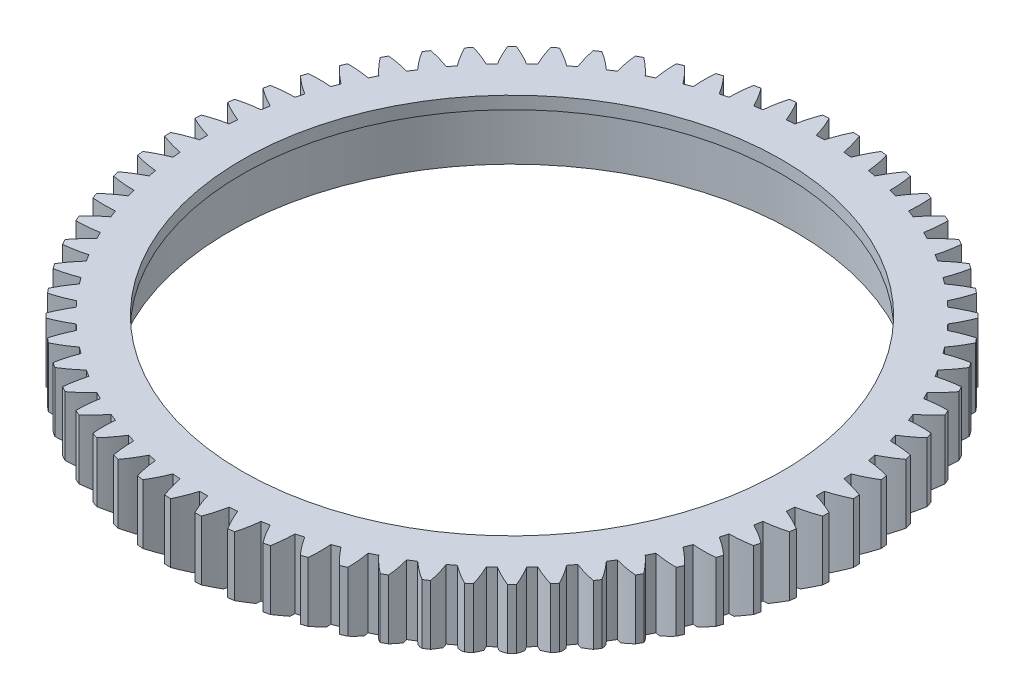
SolidWorks part; units mm, degrees
ref_plane "Front Plane" through (0, 0, 0) normal (0, 0, 1) x (1, 0, 0)
ref_plane "Top Plane" through (0, 0, 0) normal (0, 1, 0) x (1, 0, 0)
ref_plane "Right Plane" through (0, 0, 0) normal (1, 0, 0) x (0, 0, -1)
sketch "Sketch1" plane through (0, 0, 0) normal (0, 1, 0) x (1, 0, 0)
  circle A0 centre (0, 0) radius 53
  circle A1 centre (0, 0) radius 43
  dimension "D1" = 106
  dimension "D2" = 86
extrude "Boss-Extrude1" add sketch "Sketch1" along normal blind 11
sketch "Sketch3" plane through (0, 0, 0) normal (0, -1, 0) x (1, 0, 0)
  circle A0 centre (0, 0) radius 45.1
  dimension "D1" = 90.2
extrude "Cut-Extrude2" cut sketch "Sketch3" against normal blind 9
sketch "Sketch4" plane through (0, 0, 0) normal (0, -1, 0) x (1, 0, 0)
  arc A0 (-52.4646, 1.9286) -> (-49.1199, 0.6319) centre (-43.4466, 20.2271) ccw
  arc A1 (-49.1199, 0.6319) -> (-49.1199, -0.6319) centre (0, 0) ccw
  arc A2 (-49.1199, -0.6319) -> (-52.4646, -1.9286) centre (-43.4466, -20.2271) ccw
  arc A3 (-52.4646, -1.9286) -> (-52.4187, -2.9204) centre (0, 0) ccw
  arc A4 (-52.4187, -2.9204) -> (-48.9687, -3.903) centre (-45.1276, 16.1321) ccw
  arc A5 (-48.9687, -3.903) -> (-48.8521, -5.1614) centre (0, 0) ccw
  arc A6 (-48.8521, -5.1614) -> (-52.0628, -6.7612) centre (-41.3949, -24.1496) ccw
  arc A7 (-52.0628, -6.7612) -> (-51.9256, -7.7446) centre (0, 0) ccw
  arc A8 (-51.9256, -7.7446) -> (-48.3997, -8.4046) centre (-46.4235, 11.8994) ccw
  arc A9 (-48.3997, -8.4046) -> (-48.1675, -9.6469) centre (0, 0) ccw
  arc A10 (-48.1675, -9.6469) -> (-51.2169, -11.5361) centre (-38.9901, -27.866) ccw
  arc A11 (-51.2169, -11.5361) -> (-50.9896, -12.5026) centre (0, 0) ccw
  arc A12 (-50.9896, -12.5026) -> (-47.4177, -12.8345) centre (-47.3234, 7.5653) ccw
  arc A13 (-47.4177, -12.8345) -> (-47.0719, -14.0501) centre (0, 0) ccw
  arc A14 (-47.0719, -14.0501) -> (-49.934, -16.2126) centre (-36.2526, -31.3447) ccw
  arc A15 (-49.934, -16.2126) -> (-49.6184, -17.154) centre (0, 0) ccw
  arc A16 (-49.6184, -17.154) -> (-46.0312, -17.1549) centre (-47.8196, 3.1665) ccw
  arc A17 (-46.0312, -17.1549) -> (-45.5747, -18.3334) centre (0, 0) ccw
  arc A18 (-45.5747, -18.3334) -> (-48.2251, -20.7508) centre (-33.2058, -34.5559) ccw
  arc A19 (-48.2251, -20.7508) -> (-47.824, -21.659) centre (0, 0) ccw
  arc A20 (-47.824, -21.659) -> (-44.252, -21.329) centre (-47.9078, -1.2592) ccw
  arc A21 (-44.252, -21.329) -> (-43.6887, -22.4603) centre (0, 0) ccw
  arc A22 (-43.6887, -22.4603) -> (-46.1047, -25.1119) centre (-29.8758, -37.4724) ccw
  arc A23 (-46.1047, -25.1119) -> (-45.6216, -25.9793) centre (0, 0) ccw
  arc A24 (-45.6216, -25.9793) -> (-42.0953, -25.3211) centre (-47.5872, -5.6742) ccw
  arc A25 (-42.0953, -25.3211) -> (-41.43, -26.3956) centre (0, 0) ccw
  arc A26 (-41.43, -26.3956) -> (-43.591, -29.2588) centre (-26.2908, -40.0691) ccw
  arc A27 (-43.591, -29.2588) -> (-43.0299, -30.0779) centre (0, 0) ccw
  arc A28 (-43.0299, -30.0779) -> (-39.5794, -29.0971) centre (-46.8607, -10.0408) ccw
  arc A29 (-39.5794, -29.0971) -> (-38.8178, -30.1056) centre (0, 0) ccw
  arc A30 (-38.8178, -30.1056) -> (-40.7054, -33.156) centre (-22.4815, -42.324) ccw
  arc A31 (-40.7054, -33.156) -> (-40.0711, -33.9199) centre (0, 0) ccw
  arc A32 (-40.0711, -33.9199) -> (-36.7258, -32.6249) centre (-45.7343, -14.3217) ccw
  arc A33 (-36.7258, -32.6249) -> (-35.8744, -33.5589) centre (0, 0) ccw
  arc A34 (-35.8744, -33.5589) -> (-37.4725, -36.7704) centre (-18.4805, -44.2178) ccw
  arc A35 (-37.4725, -36.7704) -> (-36.7704, -37.4725) centre (0, 0) ccw
  arc A36 (-36.7704, -37.4725) -> (-33.5589, -35.8744) centre (-44.2178, -18.4805) ccw
  arc A37 (-33.5589, -35.8744) -> (-32.6249, -36.7258) centre (0, 0) ccw
  arc A38 (-32.6249, -36.7258) -> (-33.9199, -40.0711) centre (-14.3217, -45.7343) ccw
  arc A39 (-33.9199, -40.0711) -> (-33.156, -40.7054) centre (0, 0) ccw
  arc A40 (-33.156, -40.7054) -> (-30.1056, -38.8178) centre (-42.324, -22.4815) ccw
  arc A41 (-30.1056, -38.8178) -> (-29.0971, -39.5794) centre (0, 0) ccw
  arc A42 (-29.0971, -39.5794) -> (-30.0779, -43.0299) centre (-10.0408, -46.8607) ccw
  arc A43 (-30.0779, -43.0299) -> (-29.2588, -43.591) centre (0, 0) ccw
  arc A44 (-29.2588, -43.591) -> (-26.3956, -41.43) centre (-40.0691, -26.2908) ccw
  arc A45 (-26.3956, -41.43) -> (-25.3211, -42.0953) centre (0, 0) ccw
  arc A46 (-25.3211, -42.0953) -> (-25.9793, -45.6216) centre (-5.6742, -47.5872) ccw
  arc A47 (-25.9793, -45.6216) -> (-25.1119, -46.1047) centre (0, 0) ccw
  arc A48 (-25.1119, -46.1047) -> (-22.4603, -43.6887) centre (-37.4724, -29.8758) ccw
  arc A49 (-22.4603, -43.6887) -> (-21.329, -44.252) centre (0, 0) ccw
  arc A50 (-21.329, -44.252) -> (-21.659, -47.824) centre (-1.2592, -47.9078) ccw
  arc A51 (-21.659, -47.824) -> (-20.7508, -48.2251) centre (0, 0) ccw
  arc A52 (-20.7508, -48.2251) -> (-18.3334, -45.5747) centre (-34.5559, -33.2058) ccw
  arc A53 (-18.3334, -45.5747) -> (-17.1549, -46.0312) centre (0, 0) ccw
  arc A54 (-17.1549, -46.0312) -> (-17.154, -49.6184) centre (3.1665, -47.8196) ccw
  arc A55 (-17.154, -49.6184) -> (-16.2126, -49.934) centre (0, 0) ccw
  arc A56 (-16.2126, -49.934) -> (-14.0501, -47.0719) centre (-31.3447, -36.2526) ccw
  arc A57 (-14.0501, -47.0719) -> (-12.8345, -47.4177) centre (0, 0) ccw
  arc A58 (-12.8345, -47.4177) -> (-12.5026, -50.9896) centre (7.5653, -47.3234) ccw
  arc A59 (-12.5026, -50.9896) -> (-11.5361, -51.2169) centre (0, 0) ccw
  arc A60 (-11.5361, -51.2169) -> (-9.6469, -48.1675) centre (-27.866, -38.9901) ccw
  arc A61 (-9.6469, -48.1675) -> (-8.4046, -48.3997) centre (0, 0) ccw
  arc A62 (-8.4046, -48.3997) -> (-7.7446, -51.9256) centre (11.8994, -46.4235) ccw
  arc A63 (-7.7446, -51.9256) -> (-6.7612, -52.0628) centre (0, 0) ccw
  arc A64 (-6.7612, -52.0628) -> (-5.1614, -48.8521) centre (-24.1496, -41.3949) ccw
  arc A65 (-5.1614, -48.8521) -> (-3.903, -48.9687) centre (0, 0) ccw
  arc A66 (-3.903, -48.9687) -> (-2.9204, -52.4187) centre (16.1321, -45.1276) ccw
  arc A67 (-2.9204, -52.4187) -> (-1.9286, -52.4646) centre (0, 0) ccw
  arc A68 (-1.9286, -52.4646) -> (-0.6319, -49.1199) centre (-20.2271, -43.4466) ccw
  arc A69 (-0.6319, -49.1199) -> (0.6319, -49.1199) centre (0, 0) ccw
  arc A70 (0.6319, -49.1199) -> (1.9286, -52.4646) centre (20.2271, -43.4466) ccw
  arc A71 (1.9286, -52.4646) -> (2.9204, -52.4187) centre (0, 0) ccw
  arc A72 (2.9204, -52.4187) -> (3.903, -48.9687) centre (-16.1321, -45.1276) ccw
  arc A73 (3.903, -48.9687) -> (5.1614, -48.8521) centre (0, 0) ccw
  arc A74 (5.1614, -48.8521) -> (6.7612, -52.0628) centre (24.1496, -41.3949) ccw
  arc A75 (6.7612, -52.0628) -> (7.7446, -51.9256) centre (0, 0) ccw
  arc A76 (7.7446, -51.9256) -> (8.4046, -48.3997) centre (-11.8994, -46.4235) ccw
  arc A77 (8.4046, -48.3997) -> (9.6469, -48.1675) centre (0, 0) ccw
  arc A78 (9.6469, -48.1675) -> (11.5361, -51.2169) centre (27.866, -38.9901) ccw
  arc A79 (11.5361, -51.2169) -> (12.5026, -50.9896) centre (0, 0) ccw
  arc A80 (12.5026, -50.9896) -> (12.8345, -47.4177) centre (-7.5653, -47.3234) ccw
  arc A81 (12.8345, -47.4177) -> (14.0501, -47.0719) centre (0, 0) ccw
  arc A82 (14.0501, -47.0719) -> (16.2126, -49.934) centre (31.3447, -36.2526) ccw
  arc A83 (16.2126, -49.934) -> (17.154, -49.6184) centre (0, 0) ccw
  arc A84 (17.154, -49.6184) -> (17.1549, -46.0312) centre (-3.1665, -47.8196) ccw
  arc A85 (17.1549, -46.0312) -> (18.3334, -45.5747) centre (0, 0) ccw
  arc A86 (18.3334, -45.5747) -> (20.7508, -48.2251) centre (34.5559, -33.2058) ccw
  arc A87 (20.7508, -48.2251) -> (21.659, -47.824) centre (0, 0) ccw
  arc A88 (21.659, -47.824) -> (21.329, -44.252) centre (1.2592, -47.9078) ccw
  arc A89 (21.329, -44.252) -> (22.4603, -43.6887) centre (0, 0) ccw
  arc A90 (22.4603, -43.6887) -> (25.1119, -46.1047) centre (37.4724, -29.8758) ccw
  arc A91 (25.1119, -46.1047) -> (25.9793, -45.6216) centre (0, 0) ccw
  arc A92 (25.9793, -45.6216) -> (25.3211, -42.0953) centre (5.6742, -47.5872) ccw
  arc A93 (25.3211, -42.0953) -> (26.3956, -41.43) centre (0, 0) ccw
  arc A94 (26.3956, -41.43) -> (29.2588, -43.591) centre (40.0691, -26.2908) ccw
  arc A95 (29.2588, -43.591) -> (30.0779, -43.0299) centre (0, 0) ccw
  arc A96 (30.0779, -43.0299) -> (29.0971, -39.5794) centre (10.0408, -46.8607) ccw
  arc A97 (29.0971, -39.5794) -> (30.1056, -38.8178) centre (0, 0) ccw
  arc A98 (30.1056, -38.8178) -> (33.156, -40.7054) centre (42.324, -22.4815) ccw
  arc A99 (33.156, -40.7054) -> (33.9199, -40.0711) centre (0, 0) ccw
  arc A100 (33.9199, -40.0711) -> (32.6249, -36.7258) centre (14.3217, -45.7343) ccw
  arc A101 (32.6249, -36.7258) -> (33.5589, -35.8744) centre (0, 0) ccw
  arc A102 (33.5589, -35.8744) -> (36.7704, -37.4725) centre (44.2178, -18.4805) ccw
  arc A103 (36.7704, -37.4725) -> (37.4725, -36.7704) centre (0, 0) ccw
  arc A104 (37.4725, -36.7704) -> (35.8744, -33.5589) centre (18.4805, -44.2178) ccw
  arc A105 (35.8744, -33.5589) -> (36.7258, -32.6249) centre (0, 0) ccw
  arc A106 (36.7258, -32.6249) -> (40.0711, -33.9199) centre (45.7343, -14.3217) ccw
  arc A107 (40.0711, -33.9199) -> (40.7054, -33.156) centre (0, 0) ccw
  arc A108 (40.7054, -33.156) -> (38.8178, -30.1056) centre (22.4815, -42.324) ccw
  arc A109 (38.8178, -30.1056) -> (39.5794, -29.0971) centre (0, 0) ccw
  arc A110 (39.5794, -29.0971) -> (43.0299, -30.0779) centre (46.8607, -10.0408) ccw
  arc A111 (43.0299, -30.0779) -> (43.591, -29.2588) centre (0, 0) ccw
  arc A112 (43.591, -29.2588) -> (41.43, -26.3956) centre (26.2908, -40.0691) ccw
  arc A113 (41.43, -26.3956) -> (42.0953, -25.3211) centre (0, 0) ccw
  arc A114 (42.0953, -25.3211) -> (45.6216, -25.9793) centre (47.5872, -5.6742) ccw
  arc A115 (45.6216, -25.9793) -> (46.1047, -25.1119) centre (0, 0) ccw
  arc A116 (46.1047, -25.1119) -> (43.6887, -22.4603) centre (29.8758, -37.4724) ccw
  arc A117 (43.6887, -22.4603) -> (44.252, -21.329) centre (0, 0) ccw
  arc A118 (44.252, -21.329) -> (47.824, -21.659) centre (47.9078, -1.2592) ccw
  arc A119 (47.824, -21.659) -> (48.2251, -20.7508) centre (0, 0) ccw
  arc A120 (48.2251, -20.7508) -> (45.5747, -18.3334) centre (33.2058, -34.5559) ccw
  arc A121 (45.5747, -18.3334) -> (46.0312, -17.1549) centre (0, 0) ccw
  arc A122 (46.0312, -17.1549) -> (49.6184, -17.154) centre (47.8196, 3.1665) ccw
  arc A123 (49.6184, -17.154) -> (49.934, -16.2126) centre (0, 0) ccw
  arc A124 (49.934, -16.2126) -> (47.0719, -14.0501) centre (36.2526, -31.3447) ccw
  arc A125 (47.0719, -14.0501) -> (47.4177, -12.8345) centre (0, 0) ccw
  arc A126 (47.4177, -12.8345) -> (50.9896, -12.5026) centre (47.3234, 7.5653) ccw
  arc A127 (50.9896, -12.5026) -> (51.2169, -11.5361) centre (0, 0) ccw
  arc A128 (51.2169, -11.5361) -> (48.1675, -9.6469) centre (38.9901, -27.866) ccw
  arc A129 (48.1675, -9.6469) -> (48.3997, -8.4046) centre (0, 0) ccw
  arc A130 (48.3997, -8.4046) -> (51.9256, -7.7446) centre (46.4235, 11.8994) ccw
  arc A131 (51.9256, -7.7446) -> (52.0628, -6.7612) centre (0, 0) ccw
  arc A132 (52.0628, -6.7612) -> (48.8521, -5.1614) centre (41.3949, -24.1496) ccw
  arc A133 (48.8521, -5.1614) -> (48.9687, -3.903) centre (0, 0) ccw
  arc A134 (48.9687, -3.903) -> (52.4187, -2.9204) centre (45.1276, 16.1321) ccw
  arc A135 (52.4187, -2.9204) -> (52.4646, -1.9286) centre (0, 0) ccw
  arc A136 (52.4646, -1.9286) -> (49.1199, -0.6319) centre (43.4466, -20.2271) ccw
  arc A137 (49.1199, -0.6319) -> (49.1199, 0.6319) centre (0, 0) ccw
  arc A138 (49.1199, 0.6319) -> (52.4646, 1.9286) centre (43.4466, 20.2271) ccw
  arc A139 (52.4646, 1.9286) -> (52.4187, 2.9204) centre (0, 0) ccw
  arc A140 (52.4187, 2.9204) -> (48.9687, 3.903) centre (45.1276, -16.1321) ccw
  arc A141 (48.9687, 3.903) -> (48.8521, 5.1614) centre (0, 0) ccw
  arc A142 (48.8521, 5.1614) -> (52.0628, 6.7612) centre (41.3949, 24.1496) ccw
  arc A143 (52.0628, 6.7612) -> (51.9256, 7.7446) centre (0, 0) ccw
  arc A144 (51.9256, 7.7446) -> (48.3997, 8.4046) centre (46.4235, -11.8994) ccw
  arc A145 (48.3997, 8.4046) -> (48.1675, 9.6469) centre (0, 0) ccw
  arc A146 (48.1675, 9.6469) -> (51.2169, 11.5361) centre (38.9901, 27.866) ccw
  arc A147 (51.2169, 11.5361) -> (50.9896, 12.5026) centre (0, 0) ccw
  arc A148 (50.9896, 12.5026) -> (47.4177, 12.8345) centre (47.3234, -7.5653) ccw
  arc A149 (47.4177, 12.8345) -> (47.0719, 14.0501) centre (0, 0) ccw
  arc A150 (47.0719, 14.0501) -> (49.934, 16.2126) centre (36.2526, 31.3447) ccw
  arc A151 (49.934, 16.2126) -> (49.6184, 17.154) centre (0, 0) ccw
  arc A152 (49.6184, 17.154) -> (46.0312, 17.1549) centre (47.8196, -3.1665) ccw
  arc A153 (46.0312, 17.1549) -> (45.5747, 18.3334) centre (0, 0) ccw
  arc A154 (45.5747, 18.3334) -> (48.2251, 20.7508) centre (33.2058, 34.5559) ccw
  arc A155 (48.2251, 20.7508) -> (47.824, 21.659) centre (0, 0) ccw
  arc A156 (47.824, 21.659) -> (44.252, 21.329) centre (47.9078, 1.2592) ccw
  arc A157 (44.252, 21.329) -> (43.6887, 22.4603) centre (0, 0) ccw
  arc A158 (43.6887, 22.4603) -> (46.1047, 25.1119) centre (29.8758, 37.4724) ccw
  arc A159 (46.1047, 25.1119) -> (45.6216, 25.9793) centre (0, 0) ccw
  arc A160 (45.6216, 25.9793) -> (42.0953, 25.3211) centre (47.5872, 5.6742) ccw
  arc A161 (42.0953, 25.3211) -> (41.43, 26.3956) centre (0, 0) ccw
  arc A162 (41.43, 26.3956) -> (43.591, 29.2588) centre (26.2908, 40.0691) ccw
  arc A163 (43.591, 29.2588) -> (43.0299, 30.0779) centre (0, 0) ccw
  arc A164 (43.0299, 30.0779) -> (39.5794, 29.0971) centre (46.8607, 10.0408) ccw
  arc A165 (39.5794, 29.0971) -> (38.8178, 30.1056) centre (0, 0) ccw
  arc A166 (38.8178, 30.1056) -> (40.7054, 33.156) centre (22.4815, 42.324) ccw
  arc A167 (40.7054, 33.156) -> (40.0711, 33.9199) centre (0, 0) ccw
  arc A168 (40.0711, 33.9199) -> (36.7258, 32.6249) centre (45.7343, 14.3217) ccw
  arc A169 (36.7258, 32.6249) -> (35.8744, 33.5589) centre (0, 0) ccw
  arc A170 (35.8744, 33.5589) -> (37.4725, 36.7704) centre (18.4805, 44.2178) ccw
  arc A171 (37.4725, 36.7704) -> (36.7704, 37.4725) centre (0, 0) ccw
  arc A172 (36.7704, 37.4725) -> (33.5589, 35.8744) centre (44.2178, 18.4805) ccw
  arc A173 (33.5589, 35.8744) -> (32.6249, 36.7258) centre (0, 0) ccw
  arc A174 (32.6249, 36.7258) -> (33.9199, 40.0711) centre (14.3217, 45.7343) ccw
  arc A175 (33.9199, 40.0711) -> (33.156, 40.7054) centre (0, 0) ccw
  arc A176 (33.156, 40.7054) -> (30.1056, 38.8178) centre (42.324, 22.4815) ccw
  arc A177 (30.1056, 38.8178) -> (29.0971, 39.5794) centre (0, 0) ccw
  arc A178 (29.0971, 39.5794) -> (30.0779, 43.0299) centre (10.0408, 46.8607) ccw
  arc A179 (30.0779, 43.0299) -> (29.2588, 43.591) centre (0, 0) ccw
  arc A180 (29.2588, 43.591) -> (26.3956, 41.43) centre (40.0691, 26.2908) ccw
  arc A181 (26.3956, 41.43) -> (25.3211, 42.0953) centre (0, 0) ccw
  arc A182 (25.3211, 42.0953) -> (25.9793, 45.6216) centre (5.6742, 47.5872) ccw
  arc A183 (25.9793, 45.6216) -> (25.1119, 46.1047) centre (0, 0) ccw
  arc A184 (25.1119, 46.1047) -> (22.4603, 43.6887) centre (37.4724, 29.8758) ccw
  arc A185 (22.4603, 43.6887) -> (21.329, 44.252) centre (0, 0) ccw
  arc A186 (21.329, 44.252) -> (21.659, 47.824) centre (1.2592, 47.9078) ccw
  arc A187 (21.659, 47.824) -> (20.7508, 48.2251) centre (0, 0) ccw
  arc A188 (20.7508, 48.2251) -> (18.3334, 45.5747) centre (34.5559, 33.2058) ccw
  arc A189 (18.3334, 45.5747) -> (17.1549, 46.0312) centre (0, 0) ccw
  arc A190 (17.1549, 46.0312) -> (17.154, 49.6184) centre (-3.1665, 47.8196) ccw
  arc A191 (17.154, 49.6184) -> (16.2126, 49.934) centre (0, 0) ccw
  arc A192 (16.2126, 49.934) -> (14.0501, 47.0719) centre (31.3447, 36.2526) ccw
  arc A193 (14.0501, 47.0719) -> (12.8345, 47.4177) centre (0, 0) ccw
  arc A194 (12.8345, 47.4177) -> (12.5026, 50.9896) centre (-7.5653, 47.3234) ccw
  arc A195 (12.5026, 50.9896) -> (11.5361, 51.2169) centre (0, 0) ccw
  arc A196 (11.5361, 51.2169) -> (9.6469, 48.1675) centre (27.866, 38.9901) ccw
  arc A197 (9.6469, 48.1675) -> (8.4046, 48.3997) centre (0, 0) ccw
  arc A198 (8.4046, 48.3997) -> (7.7446, 51.9256) centre (-11.8994, 46.4235) ccw
  arc A199 (7.7446, 51.9256) -> (6.7612, 52.0628) centre (0, 0) ccw
  arc A200 (6.7612, 52.0628) -> (5.1614, 48.8521) centre (24.1496, 41.3949) ccw
  arc A201 (5.1614, 48.8521) -> (3.903, 48.9687) centre (0, 0) ccw
  arc A202 (3.903, 48.9687) -> (2.9204, 52.4187) centre (-16.1321, 45.1276) ccw
  arc A203 (2.9204, 52.4187) -> (1.9286, 52.4646) centre (0, 0) ccw
  arc A204 (1.9286, 52.4646) -> (0.6319, 49.1199) centre (20.2271, 43.4466) ccw
  arc A205 (0.6319, 49.1199) -> (-0.6319, 49.1199) centre (0, 0) ccw
  arc A206 (-0.6319, 49.1199) -> (-1.9286, 52.4646) centre (-20.2271, 43.4466) ccw
  arc A207 (-1.9286, 52.4646) -> (-2.9204, 52.4187) centre (0, 0) ccw
  arc A208 (-2.9204, 52.4187) -> (-3.903, 48.9687) centre (16.1321, 45.1276) ccw
  arc A209 (-3.903, 48.9687) -> (-5.1614, 48.8521) centre (0, 0) ccw
  arc A210 (-5.1614, 48.8521) -> (-6.7612, 52.0628) centre (-24.1496, 41.3949) ccw
  arc A211 (-6.7612, 52.0628) -> (-7.7446, 51.9256) centre (0, 0) ccw
  arc A212 (-7.7446, 51.9256) -> (-8.4046, 48.3997) centre (11.8994, 46.4235) ccw
  arc A213 (-8.4046, 48.3997) -> (-9.6469, 48.1675) centre (0, 0) ccw
  arc A214 (-9.6469, 48.1675) -> (-11.5361, 51.2169) centre (-27.866, 38.9901) ccw
  arc A215 (-11.5361, 51.2169) -> (-12.5026, 50.9896) centre (0, 0) ccw
  arc A216 (-12.5026, 50.9896) -> (-12.8345, 47.4177) centre (7.5653, 47.3234) ccw
  arc A217 (-12.8345, 47.4177) -> (-14.0501, 47.0719) centre (0, 0) ccw
  arc A218 (-14.0501, 47.0719) -> (-16.2126, 49.934) centre (-31.3447, 36.2526) ccw
  arc A219 (-16.2126, 49.934) -> (-17.154, 49.6184) centre (0, 0) ccw
  arc A220 (-17.154, 49.6184) -> (-17.1549, 46.0312) centre (3.1665, 47.8196) ccw
  arc A221 (-17.1549, 46.0312) -> (-18.3334, 45.5747) centre (0, 0) ccw
  arc A222 (-18.3334, 45.5747) -> (-20.7508, 48.2251) centre (-34.5559, 33.2058) ccw
  arc A223 (-20.7508, 48.2251) -> (-21.659, 47.824) centre (0, 0) ccw
  arc A224 (-21.659, 47.824) -> (-21.329, 44.252) centre (-1.2592, 47.9078) ccw
  arc A225 (-21.329, 44.252) -> (-22.4603, 43.6887) centre (0, 0) ccw
  arc A226 (-22.4603, 43.6887) -> (-25.1119, 46.1047) centre (-37.4724, 29.8758) ccw
  arc A227 (-25.1119, 46.1047) -> (-25.9793, 45.6216) centre (0, 0) ccw
  arc A228 (-25.9793, 45.6216) -> (-25.3211, 42.0953) centre (-5.6742, 47.5872) ccw
  arc A229 (-25.3211, 42.0953) -> (-26.3956, 41.43) centre (0, 0) ccw
  arc A230 (-26.3956, 41.43) -> (-29.2588, 43.591) centre (-40.0691, 26.2908) ccw
  arc A231 (-29.2588, 43.591) -> (-30.0779, 43.0299) centre (0, 0) ccw
  arc A232 (-30.0779, 43.0299) -> (-29.0971, 39.5794) centre (-10.0408, 46.8607) ccw
  arc A233 (-29.0971, 39.5794) -> (-30.1056, 38.8178) centre (0, 0) ccw
  arc A234 (-30.1056, 38.8178) -> (-33.156, 40.7054) centre (-42.324, 22.4815) ccw
  arc A235 (-33.156, 40.7054) -> (-33.9199, 40.0711) centre (0, 0) ccw
  arc A236 (-33.9199, 40.0711) -> (-32.6249, 36.7258) centre (-14.3217, 45.7343) ccw
  arc A237 (-32.6249, 36.7258) -> (-33.5589, 35.8744) centre (0, 0) ccw
  arc A238 (-33.5589, 35.8744) -> (-36.7704, 37.4725) centre (-44.2178, 18.4805) ccw
  arc A239 (-36.7704, 37.4725) -> (-37.4725, 36.7704) centre (0, 0) ccw
  arc A240 (-37.4725, 36.7704) -> (-35.8744, 33.5589) centre (-18.4805, 44.2178) ccw
  arc A241 (-35.8744, 33.5589) -> (-36.7258, 32.6249) centre (0, 0) ccw
  arc A242 (-36.7258, 32.6249) -> (-40.0711, 33.9199) centre (-45.7343, 14.3217) ccw
  arc A243 (-40.0711, 33.9199) -> (-40.7054, 33.156) centre (0, 0) ccw
  arc A244 (-40.7054, 33.156) -> (-38.8178, 30.1056) centre (-22.4815, 42.324) ccw
  arc A245 (-38.8178, 30.1056) -> (-39.5794, 29.0971) centre (0, 0) ccw
  arc A246 (-39.5794, 29.0971) -> (-43.0299, 30.0779) centre (-46.8607, 10.0408) ccw
  arc A247 (-43.0299, 30.0779) -> (-43.591, 29.2588) centre (0, 0) ccw
  arc A248 (-43.591, 29.2588) -> (-41.43, 26.3956) centre (-26.2908, 40.0691) ccw
  arc A249 (-41.43, 26.3956) -> (-42.0953, 25.3211) centre (0, 0) ccw
  arc A250 (-42.0953, 25.3211) -> (-45.6216, 25.9793) centre (-47.5872, 5.6742) ccw
  arc A251 (-45.6216, 25.9793) -> (-46.1047, 25.1119) centre (0, 0) ccw
  arc A252 (-46.1047, 25.1119) -> (-43.6887, 22.4603) centre (-29.8758, 37.4724) ccw
  arc A253 (-43.6887, 22.4603) -> (-44.252, 21.329) centre (0, 0) ccw
  arc A254 (-44.252, 21.329) -> (-47.824, 21.659) centre (-47.9078, 1.2592) ccw
  arc A255 (-47.824, 21.659) -> (-48.2251, 20.7508) centre (0, 0) ccw
  arc A256 (-48.2251, 20.7508) -> (-45.5747, 18.3334) centre (-33.2058, 34.5559) ccw
  arc A257 (-45.5747, 18.3334) -> (-46.0312, 17.1549) centre (0, 0) ccw
  arc A258 (-46.0312, 17.1549) -> (-49.6184, 17.154) centre (-47.8196, -3.1665) ccw
  arc A259 (-49.6184, 17.154) -> (-49.934, 16.2126) centre (0, 0) ccw
  arc A260 (-49.934, 16.2126) -> (-47.0719, 14.0501) centre (-36.2526, 31.3447) ccw
  arc A261 (-47.0719, 14.0501) -> (-47.4177, 12.8345) centre (0, 0) ccw
  arc A262 (-47.4177, 12.8345) -> (-50.9896, 12.5026) centre (-47.3234, -7.5653) ccw
  arc A263 (-50.9896, 12.5026) -> (-51.2169, 11.5361) centre (0, 0) ccw
  arc A264 (-51.2169, 11.5361) -> (-48.1675, 9.6469) centre (-38.9901, 27.866) ccw
  arc A265 (-48.1675, 9.6469) -> (-48.3997, 8.4046) centre (0, 0) ccw
  arc A266 (-48.3997, 8.4046) -> (-51.9256, 7.7446) centre (-46.4235, -11.8994) ccw
  arc A267 (-51.9256, 7.7446) -> (-52.0628, 6.7612) centre (0, 0) ccw
  arc A268 (-52.0628, 6.7612) -> (-48.8521, 5.1614) centre (-41.3949, 24.1496) ccw
  arc A269 (-48.8521, 5.1614) -> (-48.9687, 3.903) centre (0, 0) ccw
  arc A270 (-48.9687, 3.903) -> (-52.4187, 2.9204) centre (-45.1276, -16.1321) ccw
  arc A271 (-52.4187, 2.9204) -> (-52.4646, 1.9286) centre (0, 0) ccw
  circle A272 centre (0, 0) radius 68.1947
extrude "Cut-Extrude3" cut sketch "Sketch4" against normal blind 43
sketch "Sketch5" plane through (0, 0, 0) normal (1, 0, 0) x (0, 0, -1)
  line L0 (-54.2272, 2.4669) -> (-47.2251, -1.4886)
  line L1 (-47.2251, -1.4886) -> (-54.2272, -2.6305)
  line L2 (-54.2272, -2.6305) -> (-54.2272, 2.4669)
  line L3 (0, 0) -> (0, 15.6014) construction
  point P6 (-54.2272, 2.4669)
  point P7 (-47.2251, -1.4886)
revolve "Cut-Revolve1" cut sketch "Sketch5" angle 360 about L3
